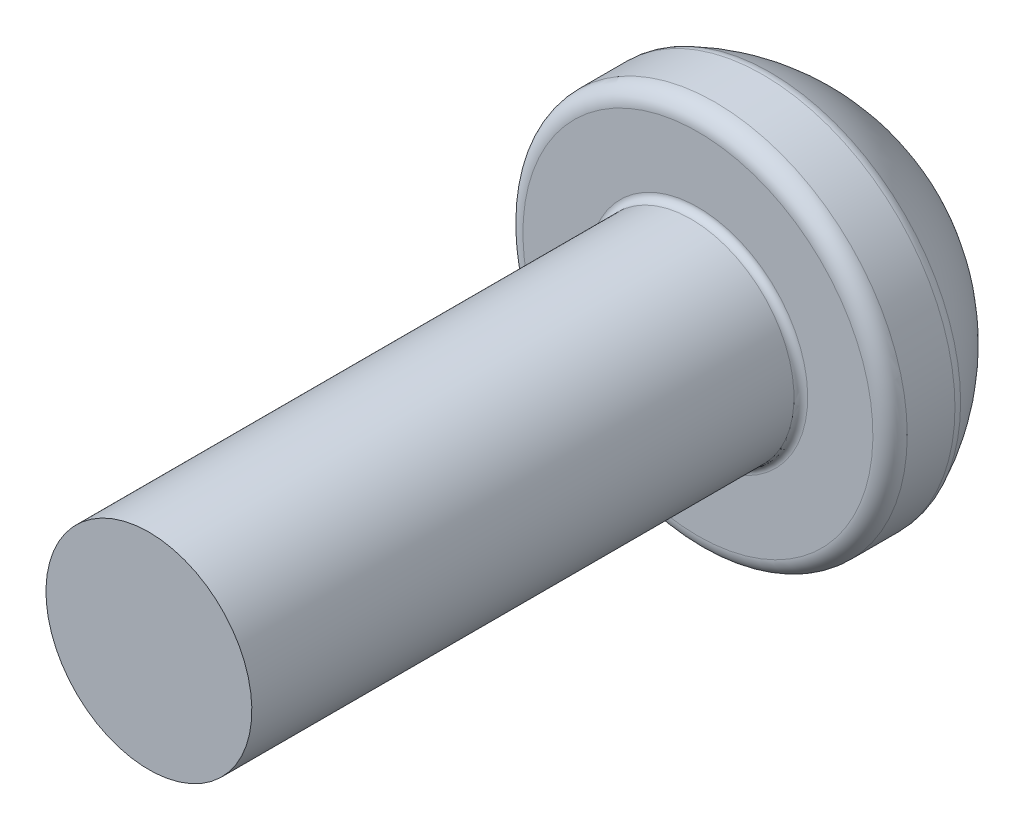
SolidWorks part; units mm, degrees
ref_plane "Plan1" through (0, 0, 0) normal (0, 0, 1) x (1, 0, 0)
ref_plane "Plan2" through (0, 0, 0) normal (0, 1, 0) x (1, 0, 0)
ref_plane "Plan3" through (0, 0, 0) normal (1, 0, 0) x (0, 0, -1)
sketch "Sketch1" plane through (0, 0, 0) normal (1, 0, 0) x (0, 0, -1)
  line L0 (2.4, 0) -> (-8, 0) construction
  line L1 (-8, 0) -> (-8, 1.5)
  line L2 (-8, 1.5) -> (0, 1.5)
  line L3 (0, 1.5) -> (0, 2.8)
  line L4 (0, 2.8) -> (1, 2.8)
  line L5 (2.4, 0) -> (2.4, 1.54)
  line L6 (2.4, 0) -> (-8, 0)
  line L7 (0, 0) -> (-0.5, 0) construction
  line L8 (0, 0) -> (0, 2.15) construction
  line L9 (0, 0) -> (0, 2.55) construction
  arc A0 (1, 2.8) -> (2.4, 1.54) centre (-0.253, 0) cw
  dimension "D1" = 3.08
  dimension "D" = 3
  dimension "L" = 8
  dimension "D2" = 1
  dimension "K" = 2.4
  dimension "DK" = 5.6
  dimension "P" = 0.5
  dimension "DW" = 5.1
revolve "Base-Revolve" add sketch "Sketch1"
cosmetic thread "Cosmetic_Thread1"
fillet "Fillet1" radius 0.1
fillet "Fillet2" radius 0.25
hole_wizard "Hole1" positions "Sketch3" profile "Sketch2"
sketch "Sketch3" plane through (0, 0, -2.4) normal (0, 0, -1) x (-1, 0, 0)
  circle A0 centre (0, 0) radius 1.54 construction
  point P0 (0, 0)
sketch "Sketch2" plane through (0, 0, -2.4) normal (1, 0, 0) x (0, 1, 0)
  line L0 (0, 0) -> (0, 1.3731)
  line L1 (0, 1.3731) -> (1.025, 1)
  line L2 (1.025, 1) -> (1.025, 0)
  line L4 (1.025, 0) -> (0, 0)
  line L6 (0, 1.3731) -> (-1.025, 1) construction
  line L7 (0, -4.2442) -> (0, 117.3081) construction
  dimension "Diameter" = 2.05
  dimension "Depth" = 1
  dimension "Drill Angle" = 140
sketch "Sketch4" plane through (0, 0, -2.4) normal (0, 0, -1) x (-1, 0, 0)
  line L0 (0, 1.4) -> (0, -1.4) construction
  line L1 (0, 0) -> (0.8075, -1.3986) construction
  line L2 (0, 0) -> (-0.8075, -1.3986) construction
  line L3 (0, 0) -> (-1.615, 0) construction
  line L4 (0, 0) -> (-0.8075, 1.3986) construction
  line L5 (0, 0) -> (0.8075, 1.3986) construction
  line L6 (0, 0) -> (1.615, 0) construction
  arc A0 (1.0888, -0.88) -> (1.3065, -0.5029) centre (0, 0) ccw
  arc A1 (1.0888, -0.88) -> (0.2177, -1.383) centre (0.8075, -1.3986) ccw
  circle A2 centre (0, 0) radius 1.025 construction
  arc A3 (-0.2177, -1.383) -> (-1.0888, -0.88) centre (-0.8075, -1.3986) ccw
  arc A4 (-1.3065, -0.5029) -> (-1.3065, 0.5029) centre (-1.615, 0) ccw
  arc A5 (-1.0888, 0.88) -> (-0.2177, 1.383) centre (-0.8075, 1.3986) ccw
  arc A6 (0.2177, 1.383) -> (1.0888, 0.88) centre (0.8075, 1.3986) ccw
  arc A7 (1.3065, 0.5029) -> (1.3065, -0.5029) centre (1.615, 0) ccw
  arc A8 (1.3065, 0.5029) -> (1.0888, 0.88) centre (0, 0) ccw
  arc A9 (0.2177, 1.383) -> (-0.2177, 1.383) centre (0, 0) ccw
  arc A10 (-1.0888, 0.88) -> (-1.3065, 0.5029) centre (0, 0) ccw
  arc A11 (-1.3065, -0.5029) -> (-1.0888, -0.88) centre (0, 0) ccw
  arc A12 (-0.2177, -1.383) -> (0.2177, -1.383) centre (0, 0) ccw
  dimension "AE" = 2.8
  dimension "EE" = 0.59
  dimension "D2" = 30
  dimension "D4" = 30
  dimension "D5" = 30
  dimension "D6" = 30
extrude "Cut-Extrude1" cut sketch "Sketch4" against normal blind 1
equation "\"D2@Sketch1\" = \"Depth@Sketch2\""
equation "\"D1@Sketch1\" = 1.1*\"AE@Sketch4\""
equation "\"D1@Cosmetic_Thread1\" = \"D@Sketch1\"-(1.0825*\"P@Sketch1\")"
equation "\"D1@Fillet2\" = (\"DK@Sketch1\"-\"DW@Sketch1\")/2"
equation "\"T@Cut-Extrude1\" = \"Depth@Sketch2\""
